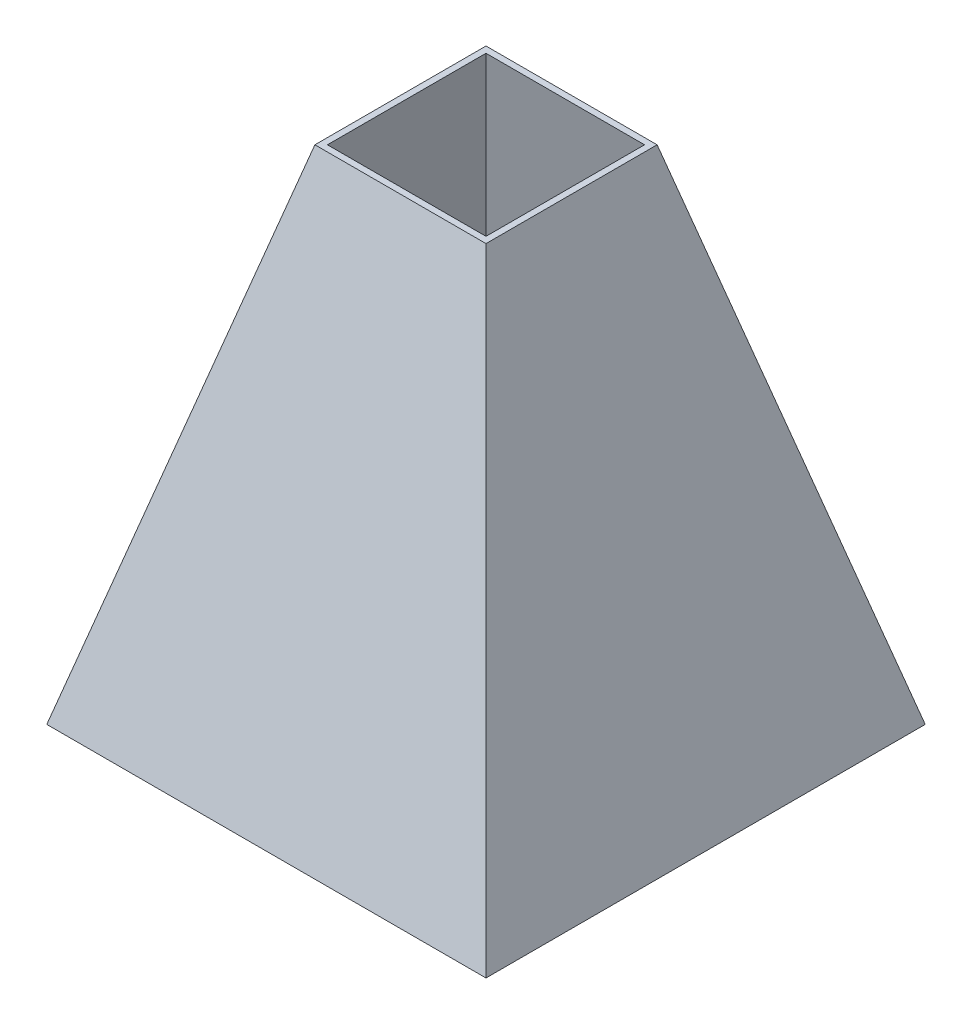
SolidWorks part; units mm, degrees
ref_plane "Front Plane" through (0, 0, 0) normal (0, 0, 1) x (1, 0, 0)
ref_plane "Top Plane" through (0, 0, 0) normal (0, 1, 0) x (1, 0, 0)
ref_plane "Right Plane" through (0, 0, 0) normal (1, 0, 0) x (0, 0, -1)
sketch "Sketch1" plane through (0, 0, 0) normal (0, 1, 0) x (1, 0, 0)
  line L1 (-105, 105) -> (105, 105)
  line L2 (-105, 105) -> (-105, -105)
  line L3 (-105, -105) -> (105, -105)
  line L4 (105, 105) -> (105, -105)
  line L5 (-105, 105) -> (105, -105) construction
  line L6 (-105, -105) -> (105, 105) construction
  point P0 (0, 0)
  dimension "D1" = 210
  dimension "D2" = 210
ref_plane "Plane1" through (0, 240, 0) normal (0, 1, 0) x (1, 0, 0)
sketch "Sketch2" plane through (0, 240, 0) normal (0, 1, 0) x (1, 0, 0)
  line L1 (-40.905, 40.905) -> (40.905, 40.905)
  line L2 (-40.905, 40.905) -> (-40.905, -40.905)
  line L3 (-40.905, -40.905) -> (40.905, -40.905)
  line L4 (40.905, 40.905) -> (40.905, -40.905)
  line L5 (-40.905, 40.905) -> (40.905, -40.905) construction
  line L6 (-40.905, -40.905) -> (40.905, 40.905) construction
  point P0 (0, 0)
  dimension "D1" = 81.81
  dimension "D2" = 81.81
loft "Loft1" add profiles "Sketch2", "Sketch1"
sketch "Sketch4" plane through (0, 240, 0) normal (0, 1, 0) x (1, 0, 0)
  line L8 (37.905, -37.905) -> (37.905, 37.905)
  line L9 (37.905, 37.905) -> (-37.905, 37.905)
  line L10 (-37.905, 37.905) -> (-37.905, -37.905)
  line L11 (-37.905, -37.905) -> (37.905, -37.905)
  line L12 (37.905, -37.905) -> (37.905, 37.905)
  line L13 (37.905, 37.905) -> (-37.905, 37.905)
  line L14 (-37.905, 37.905) -> (-37.905, -37.905)
  line L15 (-37.905, -37.905) -> (37.905, -37.905)
  dimension "D1" = 3
sketch "Sketch5" plane through (0, 0, 0) normal (0, -1, 0) x (1, 0, 0)
  line L8 (102, -102) -> (102, 102)
  line L9 (102, 102) -> (-102, 102)
  line L10 (-102, 102) -> (-102, -102)
  line L11 (-102, -102) -> (102, -102)
  line L12 (102, -102) -> (102, 102)
  line L13 (102, 102) -> (-102, 102)
  line L14 (-102, 102) -> (-102, -102)
  line L15 (-102, -102) -> (102, -102)
  dimension "D1" = 3
loft "Cut-Loft1" cut profiles "Sketch5", "Sketch4"
